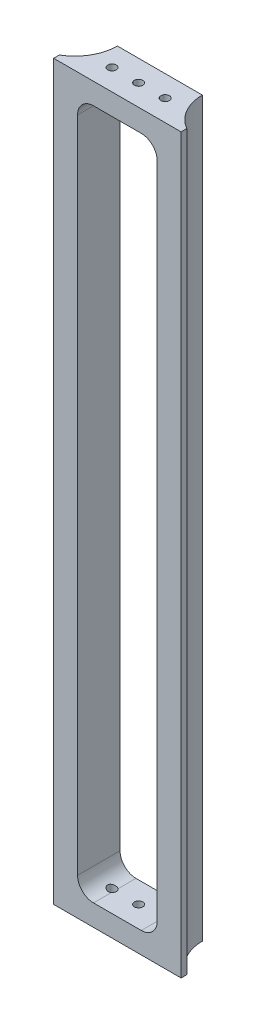
SolidWorks part; units mm, degrees
ref_plane "Front Plane" through (0, 0, 0) normal (0, 0, 1) x (1, 0, 0)
ref_plane "Top Plane" through (0, 0, 0) normal (0, 1, 0) x (1, 0, 0)
ref_plane "Right Plane" through (0, 0, 0) normal (1, 0, 0) x (0, 0, -1)
sketch "Sketch1" plane through (0, 0, 0) normal (0, 1, 0) x (1, 0, 0)
  line L1 (-66.2839, 27.3779) -> (-15.4839, 27.3779)
  line L3 (-78.9839, 1.9779) -> (-2.7839, 1.9779)
  line L4 (-78.9839, 5.3808) -> (-78.9839, 1.9779)
  line L6 (-2.7839, 5.3808) -> (-2.7839, 1.9779)
  arc A0 (-78.9839, 5.3808) -> (-66.2839, 27.3779) centre (-91.6839, 27.3779) ccw
  arc A1 (-15.4839, 27.3779) -> (-2.7839, 5.3808) centre (9.9161, 27.3779) ccw
  dimension "D2" = 25.4
  dimension "D5" = 25.4
  dimension "D1" = 101.6
  dimension "D3" = 76.2
  dimension "D4" = 12.7
  dimension "D6" = 25.4
extrude "Boss-Extrude2" add sketch "Sketch1" along normal blind 438.15
sketch "Sketch6" plane through (0, 0, -27.3779) normal (0, 0, -1) x (-1, 0, 0)
  line L0 (15.4839, 438.15) -> (66.2839, 438.15) construction
  line L1 (26.5964, 425.45) -> (55.1714, 425.45)
  line L2 (17.0714, 415.925) -> (17.0714, 22.225)
  line L3 (26.5964, 12.7) -> (55.1714, 12.7)
  line L4 (64.6964, 415.925) -> (64.6964, 22.225)
  line L5 (15.4839, 0) -> (66.2839, 0) construction
  line L6 (15.4839, 438.15) -> (15.4839, 0) construction
  line L7 (66.2839, 438.15) -> (66.2839, 0) construction
  arc A0 (55.1714, 12.7) -> (64.6964, 22.225) centre (55.1714, 22.225) ccw
  arc A1 (17.0714, 22.225) -> (26.5964, 12.7) centre (26.5964, 22.225) ccw
  arc A2 (26.5964, 425.45) -> (17.0714, 415.925) centre (26.5964, 415.925) ccw
  arc A3 (55.1714, 425.45) -> (64.6964, 415.925) centre (55.1714, 415.925) cw
  dimension "D5" = 9.525
  dimension "D1" = 12.7
  dimension "D2" = 12.7
  dimension "D3" = 1.5875
  dimension "D4" = 1.5875
extrude "Cut-Extrude1" cut sketch "Sketch6" against normal through all
hole_wizard "1/4-20 Tapped Hole1" positions "Sketch3" profile "Sketch2" tap size "1/4-20" standard "ANSI Inch"
sketch "Sketch3" plane through (0, 0, 0) normal (0, -1, 0) x (-1, 0, 0)
  line L0 (78.9839, 1.9779) -> (2.7839, 1.9779) construction
  line L1 (15.4839, 27.3779) -> (66.2839, 27.3779) construction
  point P0 (40.8839, 14.6779)
  point P2 (56.7589, 14.6779)
  point P4 (25.0089, 14.6779)
  point P14 (40.8839, 27.3779)
  dimension "D1" = 15.875
  dimension "D2" = 15.875
  dimension "D3" = 12.7
cosmetic thread "Hole Thread1" parameters "D2"=6.35
cosmetic thread "Hole Thread2" parameters "D2"=6.35
cosmetic thread "Hole Thread3" parameters "D2"=6.35
sketch "Sketch2" plane through (-40.8839, 0, -14.6779) normal (1, 0, 0) x (0, 0, -1)
  line L0 (0, 0) -> (0, 12.7)
  line L1 (0, 12.7) -> (2.5527, 12.7)
  line L2 (2.5527, 12.7) -> (2.5527, 0)
  line L5 (2.5527, 0) -> (0, 0)
  line L11 (0, -6.35) -> (0, 107.95) construction
  dimension "Thru Tap Drill Dia." = 5.1054
  dimension "Thru Tap Drill Depth" = 12.7
hole_wizard "1/4-20 Tapped Hole2" positions "Sketch5" profile "Sketch4" tap size "1/4-20" standard "ANSI Inch"
sketch "Sketch5" plane through (0, 438.15, 0) normal (0, 1, 0) x (1, 0, 0)
  line L0 (-15.4839, 27.3779) -> (-66.2839, 27.3779) construction
  line L1 (-78.9839, 1.9779) -> (-2.7839, 1.9779) construction
  point P0 (-56.7589, 14.6779)
  point P2 (-40.8839, 14.6779)
  point P4 (-25.0089, 14.6779)
  point P10 (-40.8839, 27.3779)
  dimension "D1" = 15.875
  dimension "D2" = 15.875
  dimension "D3" = 12.7
cosmetic thread "Hole Thread4" parameters "D2"=6.35
cosmetic thread "Hole Thread5" parameters "D2"=6.35
cosmetic thread "Hole Thread6" parameters "D2"=6.35
sketch "Sketch4" plane through (-56.7589, 438.15, -14.6779) normal (1, 0, 0) x (0, 0, 1)
  line L0 (0, 0) -> (0, 12.8332)
  line L1 (0, 12.8332) -> (2.5527, 12.8332)
  line L2 (2.5527, 12.8332) -> (2.5527, 0)
  line L5 (2.5527, 0) -> (0, 0)
  line L11 (0, -6.35) -> (0, 107.95) construction
  dimension "Thru Tap Drill Dia." = 5.1054
  dimension "Thru Tap Drill Depth" = 12.8332
